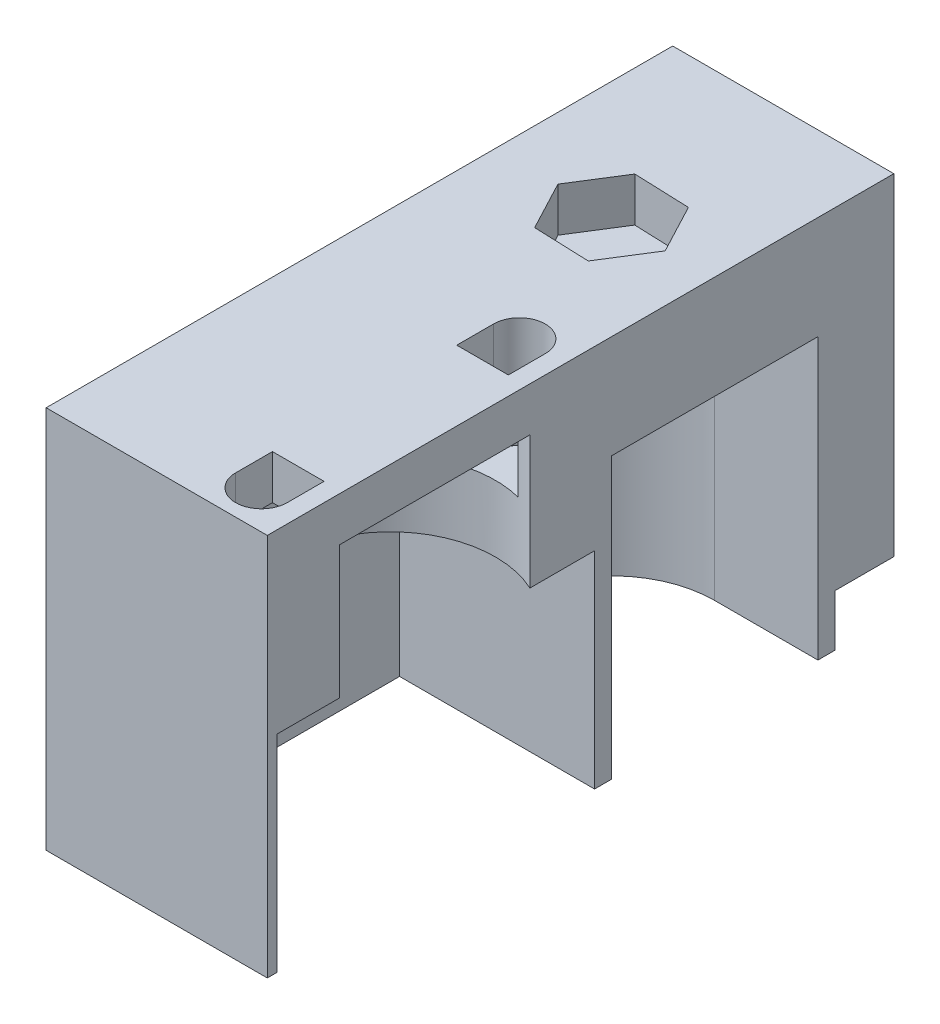
SolidWorks part; units mm, degrees
ref_plane "Спереди" through (0, 0, 0) normal (0, 0, 1) x (1, 0, 0)
ref_plane "Сверху" through (0, 0, 0) normal (0, 1, 0) x (1, 0, 0)
ref_plane "Справа" through (0, 0, 0) normal (1, 0, 0) x (0, 0, -1)
sketch "Sketch1" plane through (0, 0, 0) normal (0, 0, 1) x (1, 0, 0)
  line L0 (-504, 0) -> (-504, 60) construction
  line L1 (-500, 56) -> (-470, 56)
  line L2 (-500, 56) -> (-500, 4)
  line L3 (-500, 4) -> (-470, 4)
  line L4 (-470, 56) -> (-470, 4)
  line L5 (-504, 60) -> (4, 60) construction
  line L6 (4, 0) -> (-504, 0) construction
  line L7 (-469, 15.9004) -> (-469, 5.5) construction
  dimension "D1" = 4
  dimension "D2" = 4
  dimension "D3" = 4
  dimension "D4" = 1
extrude "Boss-Extrude1" add sketch "Sketch1" along normal blind 85
sketch "Sketch2" plane through (0, 50, 0) normal (0, 1, 0) x (1, 0, 0)
  circle A0 centre (-475.9981, -62.3) radius 14.25
  dimension "D1" = 28.5
extrude "Cut-Extrude1" cut sketch "Sketch2" against normal blind 51
sketch "Sketch3" plane through (0, 4, 0) normal (0, -1, 0) x (1, 0, 0)
  circle A0 centre (-483.9981, 62.3) radius 11.2181
extrude "Cut-Extrude2" cut sketch "Sketch3" against normal blind 27
sketch "Sketch4" plane through (0, 4, 0) normal (0, -1, 0) x (-1, 0, 0)
  line L0 (470, -49.3739) -> (470, 0) construction
  line L1 (496.4545, -83.7) -> (470, -83.7)
  line L2 (496.4545, -83.7) -> (496.4545, -40.6)
  line L3 (496.4545, -40.6) -> (470, -40.6)
  line L4 (470, -83.7) -> (470, -40.6)
  line L5 (500, -85) -> (470, -85) construction
  dimension "D1" = 1.3
  dimension "D2" = 43.1
sketch "Sketch5" plane through (0, 56, 0) normal (0, 1, 0) x (1, 0, 0)
  line L1 (-488.0262, -30.7012) -> (-480.4683, -30.9867)
  line L2 (-480.4683, -30.9867) -> (-476.4421, -24.5841)
  line L3 (-476.4421, -24.5841) -> (-479.9738, -17.896)
  line L4 (-479.9738, -17.896) -> (-487.5317, -17.6105)
  line L5 (-487.5317, -17.6105) -> (-491.5579, -24.0131)
  line L6 (-491.5579, -24.0131) -> (-488.0262, -30.7012)
  circle A0 centre (-484, -24.2986) radius 6.55 construction
extrude "Cut-Extrude3" cut sketch "Sketch5" against normal blind 6
sketch "Sketch6" plane through (0, 56, 0) normal (0, 1, 0) x (1, 0, 0)
  line L0 (-472.4981, -79.8) -> (-472.4981, -74.8)
  line L1 (-472.4981, -74.8) -> (-479.4981, -74.8)
  line L2 (-479.4981, -79.8) -> (-479.4981, -74.8)
  line L3 (-472.4981, -44.8) -> (-472.4981, -49.8)
  line L4 (-479.4981, -44.8) -> (-479.4981, -49.8)
  line L5 (-479.4981, -49.8) -> (-472.4981, -49.8)
  arc A0 (-472.4981, -44.8) -> (-479.4981, -44.8) centre (-475.9981, -44.8) ccw
  arc A1 (-479.4981, -79.8) -> (-472.4981, -79.8) centre (-475.9981, -79.8) ccw
  dimension "D2" = 7
  dimension "D3" = 5
  dimension "D4" = 5
extrude "Cut-Extrude4" cut sketch "Sketch6" against normal blind 15
extrude "Cut-Extrude5" cut sketch "Sketch4" against normal blind 28
ref_plane "Plane1" through (0, 42, 0) normal (0, 1, 0) x (1, 0, 0)
sketch "Sketch7" plane through (0, 42, 0) normal (0, 1, 0) x (1, 0, 0)
  line L0 (-484, -10.2986) -> (-469.569, -10.2986)
  line L1 (-469.569, -10.2986) -> (-469.569, -38.2986)
  line L2 (-469.569, -38.2986) -> (-484, -38.2986)
  arc A0 (-484, -10.2986) -> (-484, -38.2986) centre (-484, -24.2986) ccw
  dimension "D1" = 28
extrude "Cut-Extrude6" cut sketch "Sketch7" against normal blind 46
sketch "Sketch8" plane through (0, 0, 0) normal (0, 0, -1) x (-1, 0, 0)
  line L0 (500, 4) -> (470, 4) construction
  line L1 (470, 4) -> (495, 4)
  line L2 (470, 4) -> (470, 11)
  line L3 (470, 11) -> (495, 11)
  line L4 (495, 4) -> (495, 11)
  line L5 (470, 4) -> (470, 56) construction
  dimension "D1" = 25
  dimension "D2" = 7
extrude "Cut-Extrude7" cut sketch "Sketch8" against normal blind 8 contours L3 L4 L1 L2
